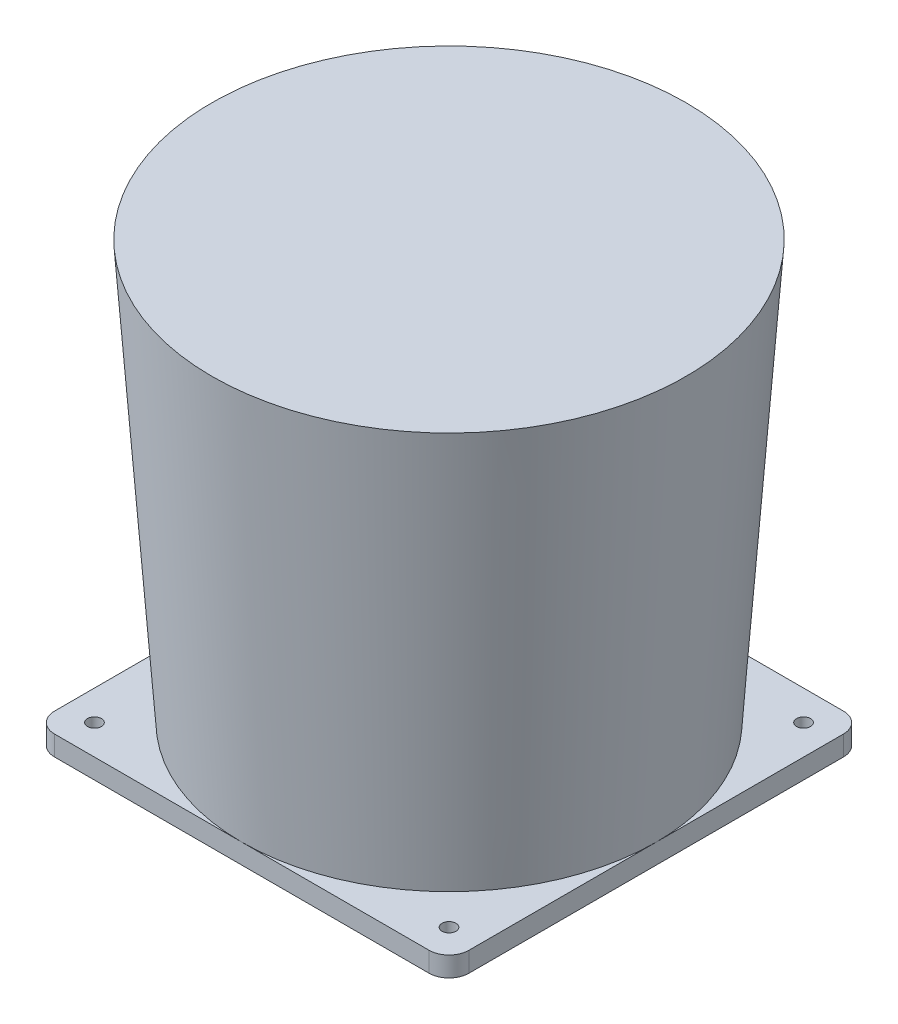
SolidWorks part; units mm, degrees
ref_plane "Front Plane" through (0, 0, 0) normal (0, 0, 1) x (1, 0, 0)
ref_plane "Top Plane" through (0, 0, 0) normal (0, 1, 0) x (1, 0, 0)
ref_plane "Right Plane" through (0, 0, 0) normal (1, 0, 0) x (0, 0, -1)
sketch "Sketch2" plane through (0, 0, 0) normal (0, 1, 0) x (1, 0, 0)
  line L0 (-94, 104) -> (94, 104)
  line L1 (-89, 89) -> (89, 89) construction
  line L2 (-89, 89) -> (-89, -89) construction
  line L3 (-89, -89) -> (89, -89) construction
  line L4 (89, 89) -> (89, -89) construction
  line L5 (-89, 89) -> (89, -89) construction
  line L6 (-89, -89) -> (89, 89) construction
  line L7 (104, 94) -> (104, -94)
  line L8 (-94, -104) -> (94, -104)
  line L9 (-104, 94) -> (-104, -94)
  line L10 (104, 104) -> (104, -104) construction
  line L11 (-104, 104) -> (104, 104) construction
  line L12 (-104, -104) -> (104, -104) construction
  line L13 (-104, 104) -> (-104, -104) construction
  arc A0 (104, 94) -> (94, 104) centre (94, 94) ccw
  arc A1 (94, -104) -> (104, -94) centre (94, -94) ccw
  arc A2 (-94, -104) -> (-104, -94) centre (-94, -94) cw
  arc A3 (-104, 94) -> (-94, 104) centre (-94, 94) cw
  circle A4 centre (-89, 89) radius 3.5
  circle A5 centre (89, 89) radius 3.5
  circle A6 centre (89, -89) radius 3.5
  circle A7 centre (-89, -89) radius 3.5
  point P0 (0, 0)
  dimension "D4" = 10
  dimension "D5" = 7
  dimension "D1" = 178
  dimension "D2" = 178
  dimension "D3" = 15
  dimension "D6" = 2
  dimension "D7" = 2
extrude "Boss-Extrude1" add sketch "Sketch2" along normal blind 10
sketch "Sketch3" plane through (0, 10, 0) normal (0, 1, 0) x (1, 0, 0)
  circle A0 centre (0, 0) radius 104
ref_plane "Plane1" through (0, 220, 0) normal (0, 1, 0) x (1, 0, 0)
sketch "Sketch4" plane through (0, 220, 0) normal (0, 1, 0) x (1, 0, 0)
  circle A0 centre (0, 0) radius 119
  dimension "D1" = 238
loft "Loft1" add profiles "Sketch4", "Sketch3"
